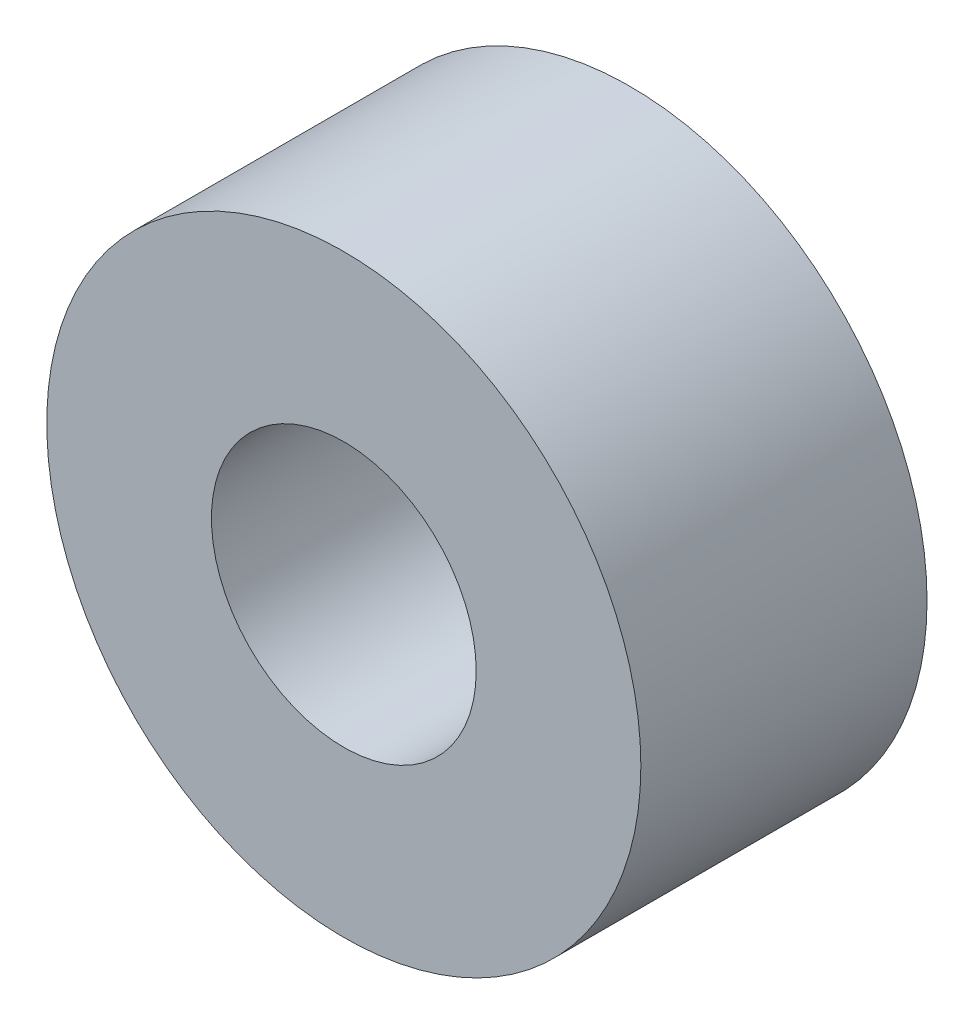
SolidWorks part; units mm, degrees
ref_plane "Front Plane" through (0, 0, 0) normal (0, 0, 1) x (1, 0, 0)
ref_plane "Top Plane" through (0, 0, 0) normal (0, 1, 0) x (1, 0, 0)
ref_plane "Right Plane" through (0, 0, 0) normal (1, 0, 0) x (0, 0, -1)
sketch "Sketch1" plane through (0, 0, 0) normal (0, 0, 1) x (1, 0, 0)
  circle A0 centre (0, 0) radius 12.5095
  circle A1 centre (0, 0) radius 5.5753
  dimension "D1" = 25.019
  dimension "D2" = 11.1506
extrude "Boss-Extrude1" add sketch "Sketch1" along normal mid plane 12.0523
